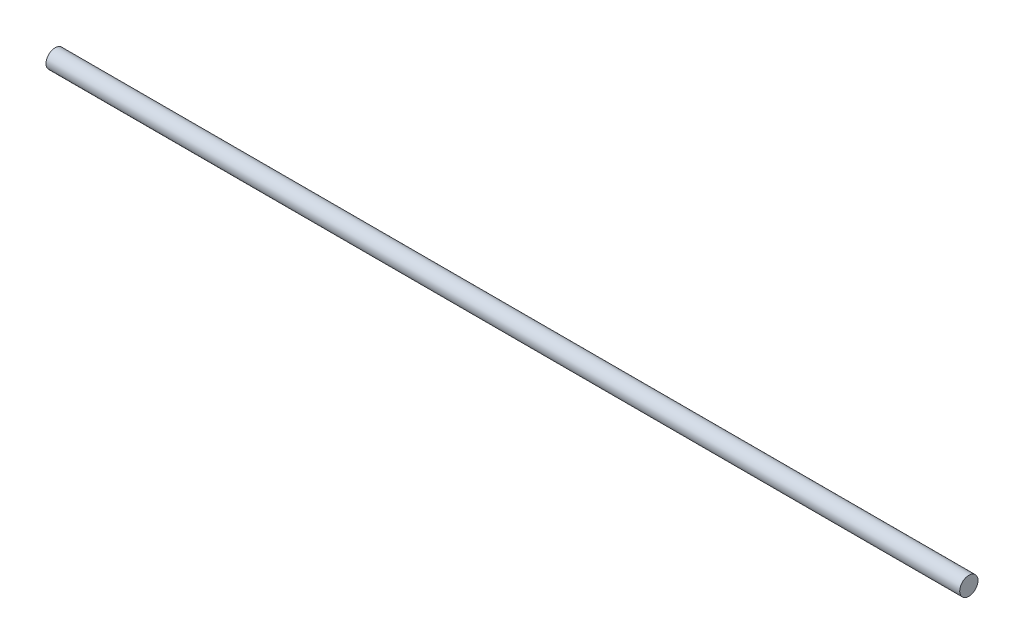
SolidWorks part; units mm, degrees
ref_plane "Front Plane" through (0, 0, 0) normal (0, 0, 1) x (1, 0, 0)
ref_plane "Top Plane" through (0, 0, 0) normal (0, 1, 0) x (1, 0, 0)
ref_plane "Right Plane" through (0, 0, 0) normal (1, 0, 0) x (0, 0, -1)
sketch "Sketch1" plane through (0, 0, 0) normal (1, 0, 0) x (0, 0, -1)
  circle A0 centre (0, 0) radius 4
  dimension "D1" = 8
extrude "Boss-Extrude1" add sketch "Sketch1" along normal blind 400
